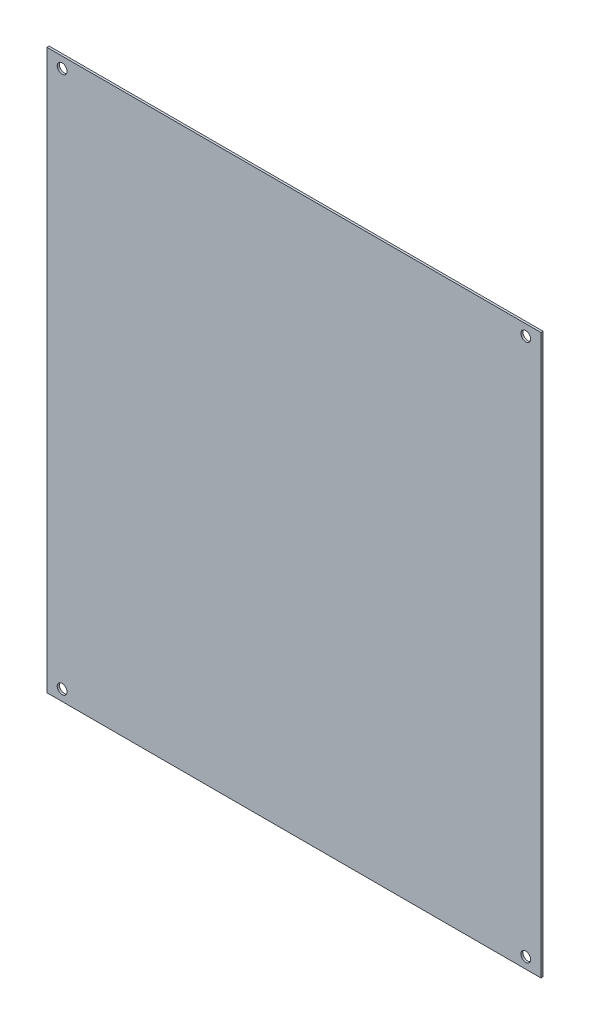
SolidWorks part; units mm, degrees
ref_plane "Спереди" through (0, 0, 0) normal (0, 0, 1) x (1, 0, 0)
ref_plane "Сверху" through (0, 0, 0) normal (0, 1, 0) x (1, 0, 0)
ref_plane "Справа" through (0, 0, 0) normal (1, 0, 0) x (0, 0, -1)
sketch "Эскиз1" plane through (0, 0, 0) normal (0, 0, 1) x (1, 0, 0)
  line L0 (0, 0) -> (37.4752, 0) construction
  line L1 (0, 0) -> (0, 27.8606) construction
  line L3 (-114, -129) -> (114, -129)
  line L4 (-114, -129) -> (-114, 129)
  line L5 (-114, 129) -> (114, 129)
  line L6 (114, -129) -> (114, 129)
  circle A0 centre (-107, 124) radius 2.25
  circle A1 centre (107, 124) radius 2.25
  circle A2 centre (107, -124) radius 2.25
  circle A3 centre (-107, -124) radius 2.25
  dimension "D3" = 214
  dimension "D4" = 4.5
  dimension "D5" = 5
  dimension "D1" = 258
  dimension "D2" = 228
extrude "Вытянуть1" add sketch "Эскиз1" along normal blind 1
